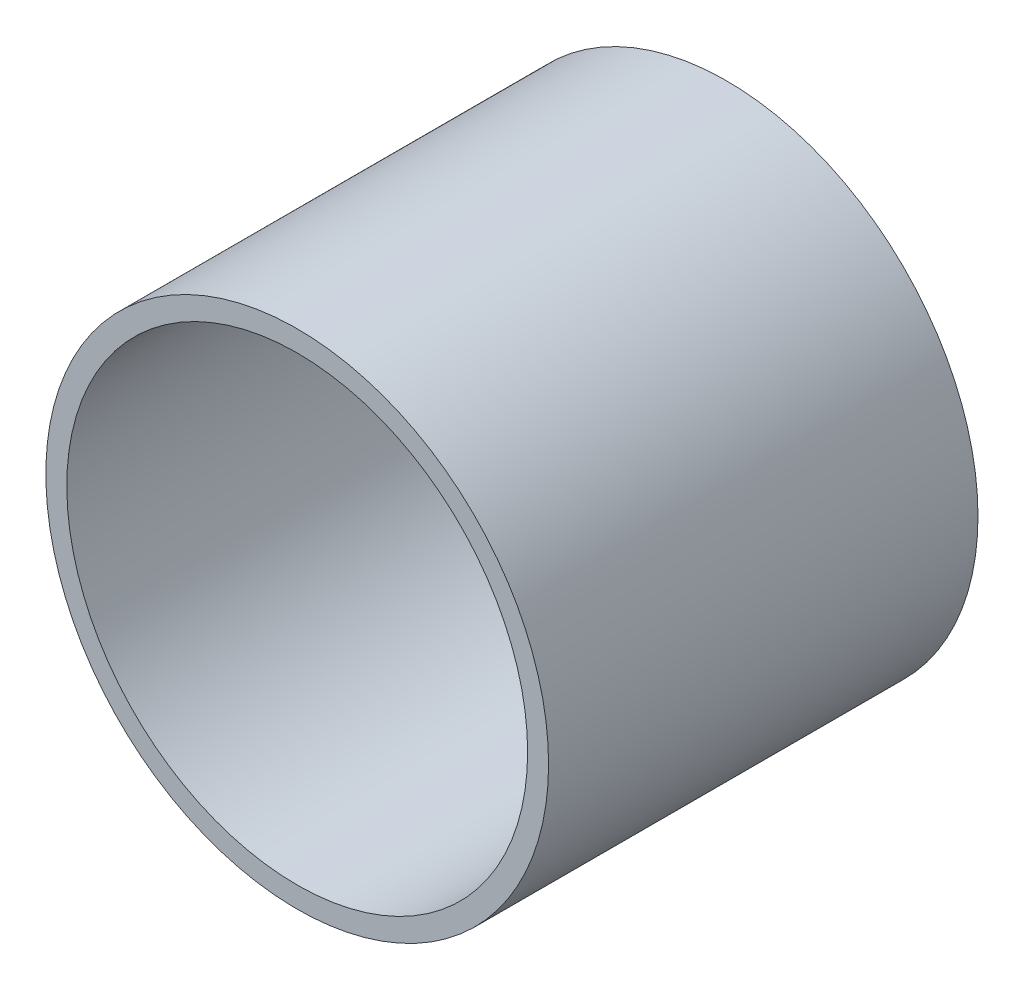
SolidWorks part; units mm, degrees
ref_plane "Front Plane" through (0, 0, 0) normal (0, 0, 1) x (1, 0, 0)
ref_plane "Top Plane" through (0, 0, 0) normal (0, 1, 0) x (1, 0, 0)
ref_plane "Right Plane" through (0, 0, 0) normal (1, 0, 0) x (0, 0, -1)
sketch "Sketch1" plane through (0, 0, 0) normal (0, 0, 1) x (1, 0, 0)
  circle A0 centre (0, 0) radius 60.96
  circle A2 centre (0, 0) radius 55.88
  dimension "D1" = 121.92
  dimension "D2" = 5.08
extrude "Boss-Extrude1" add sketch "Sketch1" along normal blind 104.14 contours A0 A2
sketch "Sketch2" plane through (0, 0, 0) normal (0, 0, -1) x (-1, 0, 0)
  line L0 (-48.26, 7.62) -> (-55.358, 7.62)
  line L1 (-48.26, -7.62) -> (-55.358, -7.62)
  circle A1 centre (-48.26, 0) radius 3.3782
  arc A4 (-48.26, -7.62) -> (-48.26, 7.62) centre (-48.26, 0) ccw
  circle A5 centre (0, 0) radius 55.88 construction
  circle A8 centre (0, 0) radius 55.88
  arc A9 (-55.358, 7.62) -> (-55.358, -7.62) centre (0, 0) ccw
  dimension "D1" = 0
  dimension "D2" = 48.26
extrude "Boss-Extrude2" add sketch "Sketch2" against normal blind 6.35
pattern_circular "CirPattern1" count 4 over 360 about axis through (0, 0, 0) along (0, 0, 1) of "Boss-Extrude2"
